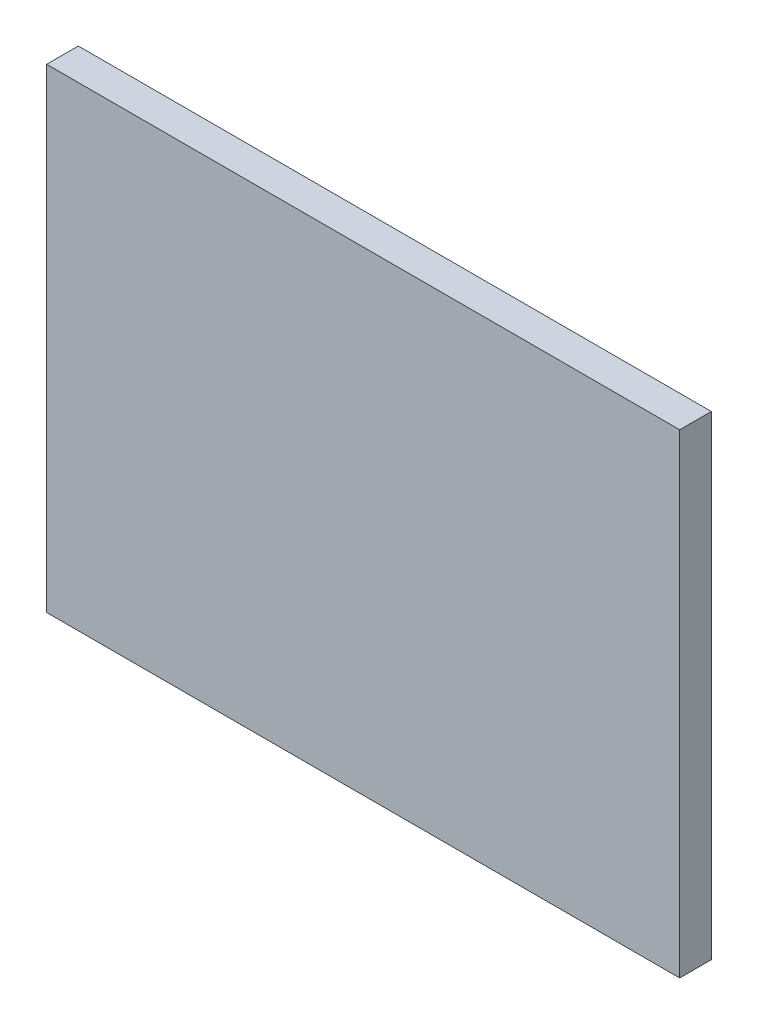
SolidWorks part; units mm, degrees
ref_plane "Front Plane" through (0, 0, 0) normal (0, 0, 1) x (1, 0, 0)
ref_plane "Top Plane" through (0, 0, 0) normal (0, 1, 0) x (1, 0, 0)
ref_plane "Right Plane" through (0, 0, 0) normal (1, 0, 0) x (0, 0, -1)
sketch "Sketch1" plane through (0, 0, 0) normal (0, 0, 1) x (1, 0, 0)
  line L1 (0, 0) -> (101.6, 0)
  line L2 (0, 0) -> (0, 76.2)
  line L3 (0, 76.2) -> (101.6, 76.2)
  line L4 (101.6, 0) -> (101.6, 76.2)
  dimension "D1" = 101.6
  dimension "D2" = 76.2
extrude "Boss-Extrude1" add sketch "Sketch1" along normal blind 5.08
